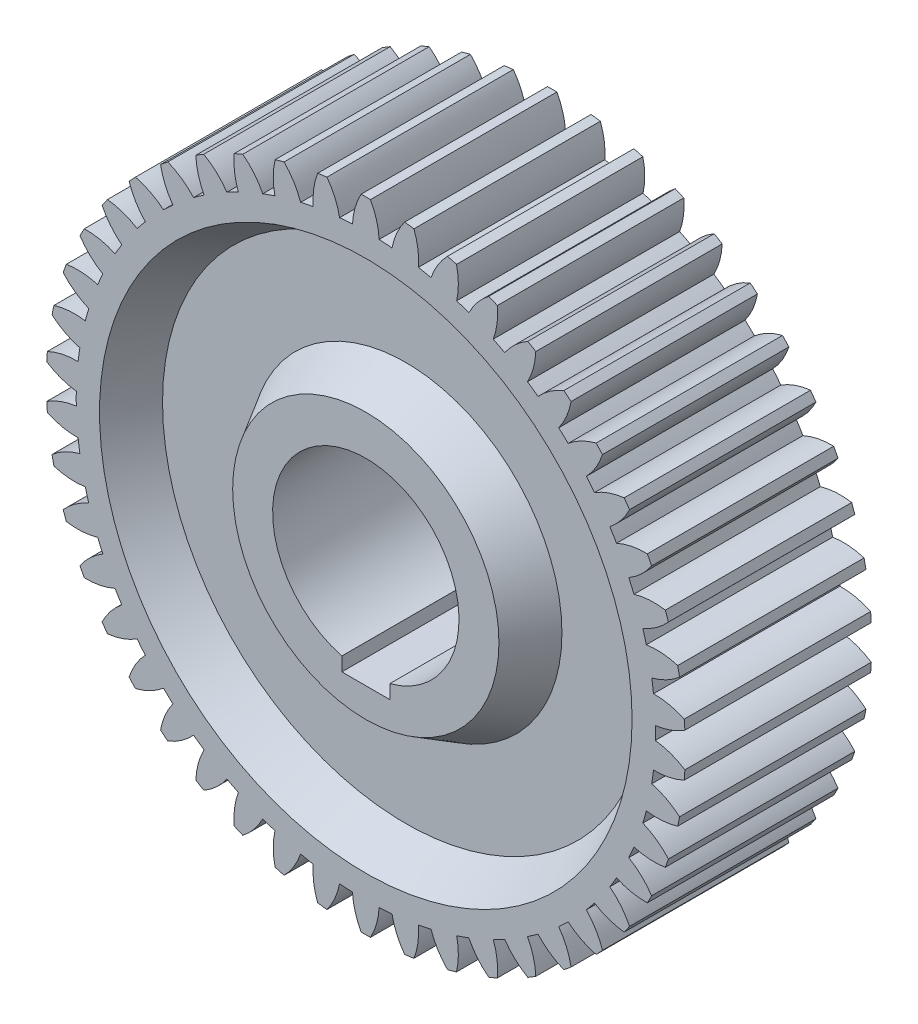
SolidWorks part; units mm, degrees
ref_plane "前视" through (0, 0, 0) normal (0, 0, 1) x (1, 0, 0)
ref_plane "上视" through (0, 0, 0) normal (0, 1, 0) x (1, 0, 0)
ref_plane "右视" through (0, 0, 0) normal (1, 0, 0) x (0, 0, -1)
sketch "草图1" plane through (0, 0, 0) normal (0, 0, 1) x (1, 0, 0)
  circle A0 centre (0, 0) radius 217.5
  dimension "D1" = 435
extrude "拉伸1" add sketch "草图1" along normal mid plane 140
sketch "草图2" plane through (0, 0, 0) normal (0, 0, 1) x (1, 0, 0)
  line L0 (0, -47.5135) -> (0, 271.5772) construction
  line L1 (0, 0) -> (-9.7796, 286.2083) construction
  line L2 (-3.5, 260.8832) -> (-3.5, 211.8105) construction
  line L3 (-10, 260.8832) -> (-10, 211.8105) construction
  circle A0 centre (0, 0) radius 217.5 construction
  arc A1 (10, 217.27) -> (-10, 217.27) centre (0, 0) ccw
  arc A2 (7.7764, 229.8685) -> (-10, 229.7825) centre (0, 0) ccw construction
  arc A3 (3.5, 239.9745) -> (-3.5, 239.9745) centre (0, 0) ccw
  arc A4 (-3.5, 239.9745) -> (-10, 217.27) centre (42.7129, 214.4617) ccw
  arc A5 (3.5, 239.9745) -> (10, 217.27) centre (-42.7129, 214.4617) cw
  point P8 (-7.8465, 229.6366)
  dimension "D1" = 460
  dimension "D2" = 480
  dimension "D3" = 1.957
  dimension "D4" = 3.5
  dimension "D5" = 10
extrude "拉伸2" add sketch "草图2" along normal mid plane 140
pattern_circular "阵列(圆周)1" count 46 over 360 about axis through (0, 0, 0) along (0, 0, 1) of "拉伸2"
sketch "草图3" plane through (0, 0, -70) normal (0, 0, 1) x (1, 0, 0)
  line L2 (-18, -67.6461) -> (-18, -78)
  line L3 (-18, -78) -> (18, -78)
  line L4 (18, -67.6461) -> (18, -78)
  arc A0 (18, -67.6461) -> (-18, -67.6461) centre (0, 0) ccw
  dimension "D1" = 140
  dimension "D2" = 36
  dimension "D3" = 78
  dimension "D4" = 18
extrude "切除-拉伸1" cut sketch "草图3" along normal through all
sketch "草图4" plane through (0, 0, -70) normal (0, 0, 1) x (1, 0, 0)
  circle A0 centre (0, 0) radius 100
  circle A1 centre (0, 0) radius 200
  dimension "D1" = 200
  dimension "D2" = 400
extrude "切除-拉伸2" cut sketch "草图4" along normal blind 30 draft 30
mirror "镜向1" about plane through (0, 0, 0) normal (0, 0, 1) of "切除-拉伸2"
sketch "草图5" plane through (0, 0, 0) normal (0, 0, 1) x (1, 0, 0)
  line L0 (0, 0) -> (-296.5381, -105.3897) construction
  circle A0 centre (0, 0) radius 230 construction
  arc A2 (-227.2907, -77.0646) -> (-224.9465, -83.6605) centre (0, 0) ccw construction
  point P7 (-226.1426, -80.3711)
  dimension "D1" = 460
